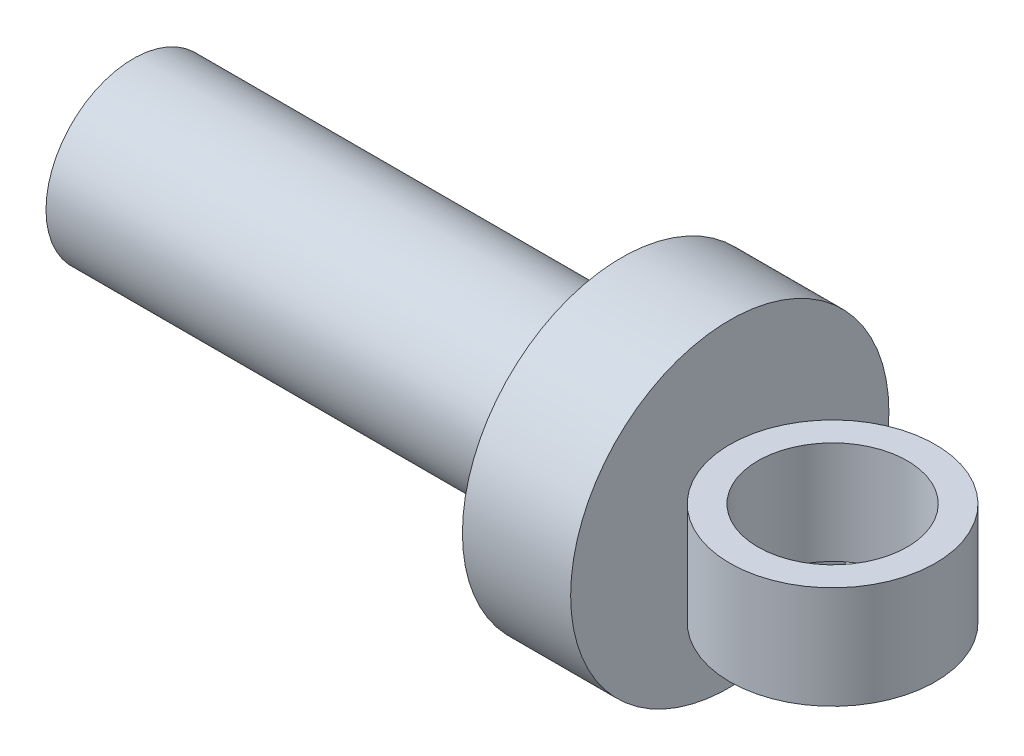
SolidWorks part; units mm, degrees
ref_plane "Front Plane" through (0, 0, 0) normal (0, 0, 1) x (1, 0, 0)
ref_plane "Top Plane" through (0, 0, 0) normal (0, 1, 0) x (1, 0, 0)
ref_plane "Right Plane" through (0, 0, 0) normal (1, 0, 0) x (0, 0, -1)
sketch "Sketch1" plane through (0, 0, 0) normal (0, 0, 1) x (1, 0, 0)
  line L0 (-116.2, 12) -> (-5, 12)
  line L1 (-5, 12) -> (-5, 0)
  line L2 (-5, 0) -> (0, 0)
  line L3 (0, 0) -> (0, 15)
  line L4 (-1, 17) -> (-116.2, 17)
  line L5 (-116.2, 17) -> (-116.2, 12)
  line L6 (0, 15) -> (0, 31)
  line L7 (0, 31) -> (-21.0804, 31)
  line L8 (-21.0804, 31) -> (-21.0804, 30)
  line L9 (-21.0804, 30) -> (-1, 30)
  line L10 (-1, 30) -> (-1, 17)
  dimension "D1" = 12
  dimension "D2" = 111.2
  dimension "D3" = 5
  dimension "D4" = 5
  dimension "D5" = 1
  dimension "D6" = 1
  dimension "D7" = 30
revolve "Revolve1" add sketch "Sketch1" angle 360 about L2
sketch "Sketch2" plane through (0, 0, 0) normal (0, 1, 0) x (1, 0, 0)
  line L0 (0, -31) -> (0, 31) construction
  circle A0 centre (20.03, 0) radius 14.555
  circle A1 centre (20.03, 0) radius 20.03
  dimension "D1" = 29.11
  dimension "D2" = 40.06
extrude "Boss-Extrude1" add sketch "Sketch2" along normal mid plane 20 separate body
